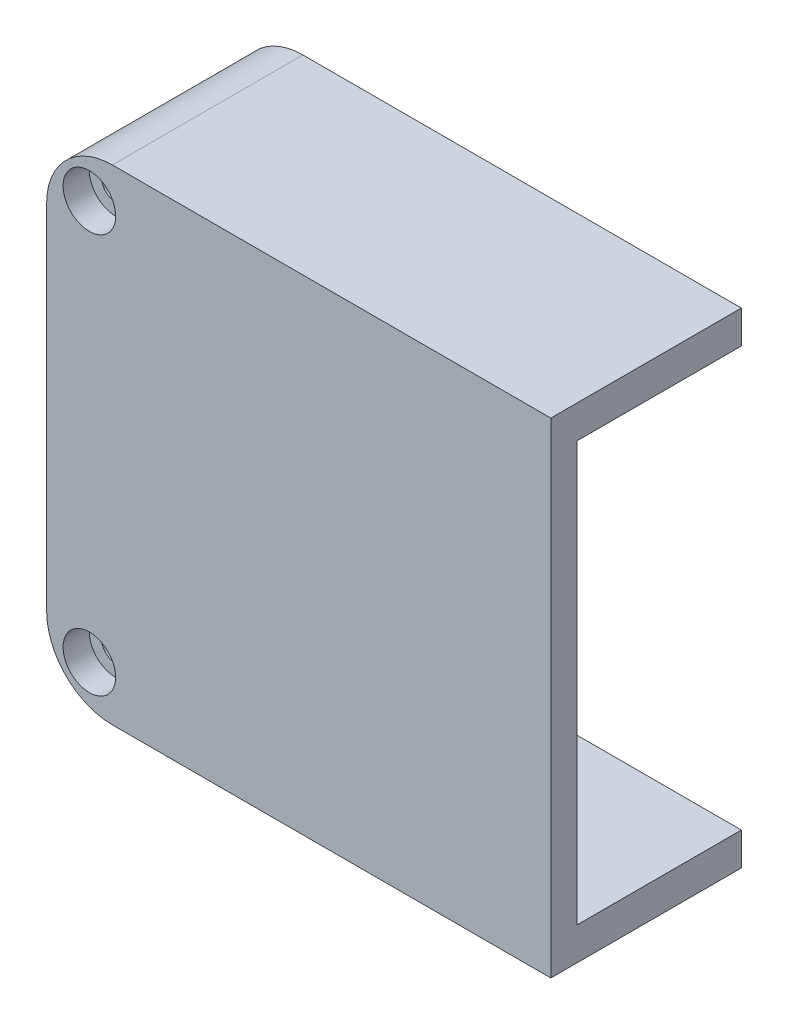
SolidWorks part; units mm, degrees
material "ABS"
ref_plane "Front Plane" through (0, 0, 0) normal (0, 0, 1) x (1, 0, 0)
ref_plane "Top Plane" through (0, 0, 0) normal (0, 1, 0) x (1, 0, 0)
ref_plane "Right Plane" through (0, 0, 0) normal (1, 0, 0) x (0, 0, -1)
sketch "Sketch1" plane through (0, 0, 0) normal (0, 0, 1) x (1, 0, 0)
  line L0 (-44.5294, 1.9513) -> (-90.4471, 1.9513) construction
  line L1 (-76.7346, -29.9473) -> (-76.7346, 33.8498)
  line L2 (-76.7346, 33.8498) -> (-5.0075, 33.8498)
  line L4 (-76.7346, -29.9473) -> (-5.0075, -29.9473)
  point P7 (-5.0075, 1.9513)
  point P8 (-76.7346, 1.9513)
extrude "Extrude-Thin1" add sketch "Sketch1" along normal blind 25 thin thin type one direction reverse wall 5
sketch "Sketch2" plane through (0, 0, 0) normal (0, 0, 1) x (1, 0, 0)
  line L0 (-68.2493, 33.8498) -> (-76.7346, 25.3645)
  line L1 (-76.7346, 33.8498) -> (-5.0075, 33.8498) construction
  line L2 (-76.7346, -29.9473) -> (-76.7346, 33.8498) construction
  line L3 (-76.7346, 25.3645) -> (-76.7346, 33.8498)
  line L4 (-76.7346, 33.8498) -> (-68.2493, 33.8498)
  line L5 (-81.7346, 1.9513) -> (-25.8882, 1.9513) construction
  line L6 (-81.7346, -34.9473) -> (-81.7346, 38.8498) construction
  line L7 (-76.7346, -29.9473) -> (-68.2493, -29.9473)
  line L8 (-76.7346, -21.462) -> (-76.7346, -29.9473)
  line L9 (-68.2493, -29.9473) -> (-76.7346, -21.462)
  dimension "D1" = 12
extrude "Boss-Extrude1" add sketch "Sketch2" along normal up to surface (25 mm away) up to face at (-42.1211, 1.9513, 25)
sketch "Sketch3" plane through (0, 0, 25) normal (0, 0, 1) x (1, 0, 0)
  line L1 (-81.7346, 38.8498) -> (-5.0075, 38.8498)
  line L2 (-81.7346, 38.8498) -> (-81.7346, -34.9473)
  line L3 (-81.7346, -34.9473) -> (-5.0075, -34.9473)
  line L4 (-5.0075, 38.8498) -> (-5.0075, -34.9473)
extrude "Boss-Extrude2" add sketch "Sketch3" along normal blind 4
fillet "Fillet1" radius 10 2 edges at (-81.7346, -34.9473, 14.5) (-81.7346, 38.8498, 14.5)
fillet "Fillet2" radius 5 4 edges at (-68.2493, -29.9473, 12.5) (-76.7346, -21.462, 12.5) (-68.2493, 33.8498, 12.5) (-76.7346, 25.3645, 12.5)
sketch "Sketch4" plane through (0, 0, 29) normal (0, 0, 1) x (1, 0, 0)
  line L0 (-81.7346, 28.8498) -> (-81.7346, -24.9473) construction
  line L1 (-5.0075, 38.8498) -> (-71.7346, 38.8498) construction
  line L2 (-81.7346, 1.9513) -> (-5.0075, 1.9513) construction
  line L3 (-5.0075, -34.9473) -> (-5.0075, 38.8498) construction
  point P0 (-75.2346, 32.3498)
  point P9 (-75.2346, -28.4473)
  dimension "D1" = 6.5
  dimension "D2" = 6.5
hole_wizard "CBORE for M4 SHCS1" positions "3DSketch1" profile "Sketch5" counterbore size "M4" standard "ANSI Metric" end condition through all
sketch3d "3DSketch1"
  point P0 (-75.2346, 32.3498, 29)
  point P3 (-75.2346, -28.4473, 29)
sketch "Sketch5" plane through (-75.2346, 32.3498, 29) normal (1, 0, 0) x (0, -1, 0)
  line L0 (0, 0) -> (0, 29)
  line L1 (0, 29) -> (2.15, 29)
  line L3 (2.15, 29) -> (2.15, 4)
  line L4 (2.15, 4) -> (4, 4)
  line L5 (4, 4) -> (4, 0)
  line L7 (4, 0) -> (0, 0)
  line L11 (0, -6.35) -> (0, 107.95) construction
  dimension "Thru Hole Dia." = 4.3
  dimension "Thru Hole Depth" = 29
  dimension "C'Bore Dia." = 8
  dimension "C'Bore Depth" = 4
